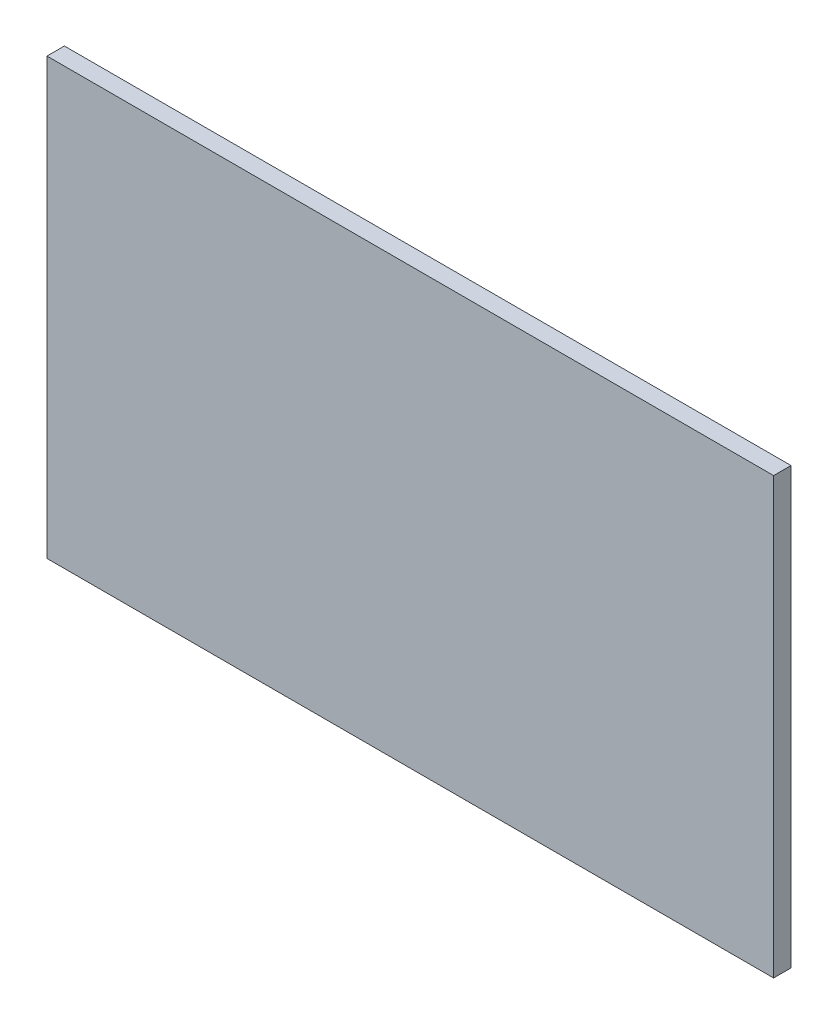
SolidWorks part; units mm, degrees
material "Beech"
ref_plane "Front Plane" through (0, 0, 0) normal (0, 0, 1) x (1, 0, 0)
ref_plane "Top Plane" through (0, 0, 0) normal (0, 1, 0) x (1, 0, 0)
ref_plane "Right Plane" through (0, 0, 0) normal (1, 0, 0) x (0, 0, -1)
sketch "Sketch1" plane through (0, 0, 0) normal (0, 0, 1) x (1, 0, 0)
  line L1 (417.5, -250) -> (-417.5, -250)
  line L2 (417.5, -250) -> (417.5, 250)
  line L3 (417.5, 250) -> (-417.5, 250)
  line L4 (-417.5, -250) -> (-417.5, 250)
  line L5 (417.5, -250) -> (-417.5, 250) construction
  line L6 (417.5, 250) -> (-417.5, -250) construction
  point P0 (0, 0)
  dimension "D1" = 835
  dimension "D2" = 500
extrude "Boss-Extrude1" add sketch "Sketch1" along normal blind 20
